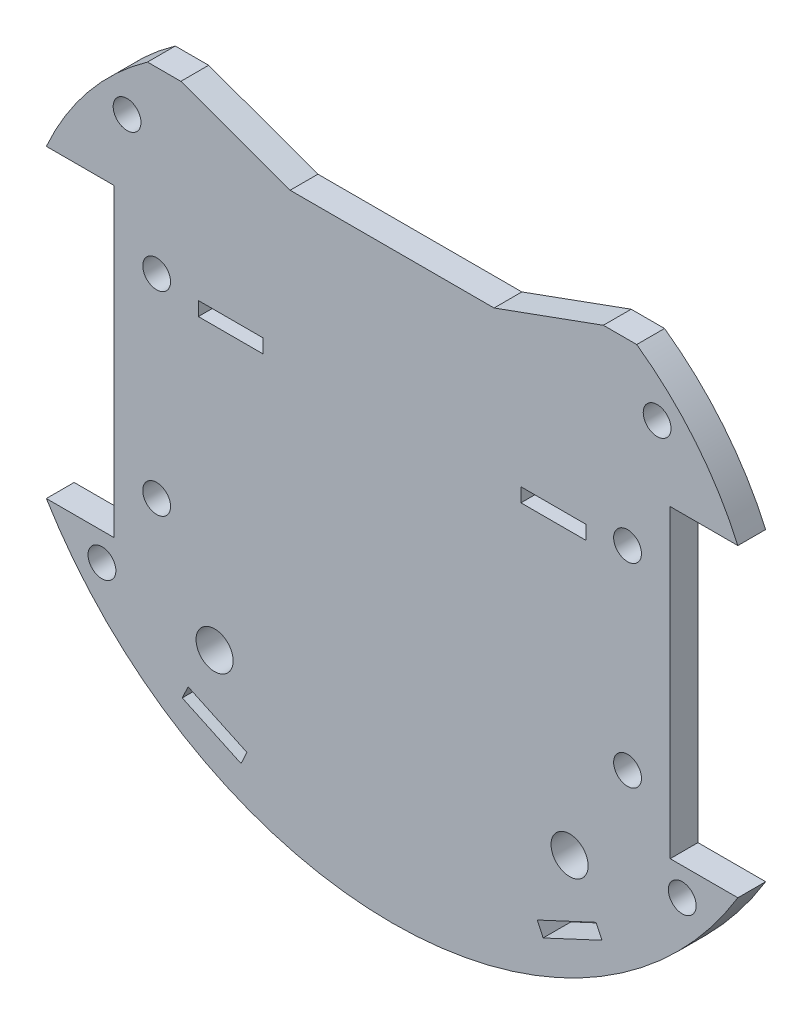
SolidWorks part; units mm, degrees
ref_plane "Front Plane" through (0, 0, 0) normal (0, 0, 1) x (1, 0, 0)
ref_plane "Top Plane" through (0, 0, 0) normal (0, 1, 0) x (1, 0, 0)
ref_plane "Right Plane" through (0, 0, 0) normal (1, 0, 0) x (0, 0, -1)
sketch "Sketch1" plane through (0, 0, 0) normal (0, 0, 1) x (1, 0, 0)
  line L2 (11, 25.5) -> (-11, 25.5)
  line L3 (-11, 25.5) -> (-22.79, 29.7803)
  line L4 (11, 25.5) -> (22.79, 29.7803)
  arc A0 (-22.79, 29.7803) -> (22.79, 29.7803) centre (0, 0) ccw
  arc A1 (-22.79, 29.7803) -> (22.79, 29.7803) centre (0, 0) ccw
  dimension "D2" = 37.5
extrude "Boss-Extrude1" add sketch "Sketch1" along normal blind 3 contours L3 A0 L4 L2
sketch "Sketch2" plane through (0, 0, 3) normal (0, 0, 1) x (1, 0, 0)
  line L0 (0, 0) -> (-25.8, 0) construction
  line L2 (0, 0) -> (0, 15.281) construction
  circle A4 centre (-25.4, 10.4969) radius 1.5
  circle A5 centre (-25.4, -10.4931) radius 1.5
  circle A6 centre (25.4, -10.4931) radius 1.5
  circle A7 centre (25.4, 10.4969) radius 1.5
  point P6 (-25.8, 0)
  dimension "D1" = 25.8
  dimension "D2" = 20.99
extrude "Cut-Extrude3" cut sketch "Sketch2" against normal blind 3
sketch "Sketch3" plane through (0, 0, 3) normal (0, 0, 1) x (1, 0, 0)
  line L1 (-30.76, 21.4493) -> (-30.76, -21.4493)
  line L3 (30.76, 21.4493) -> (30.76, -21.4493)
  arc A0 (-22.79, 29.7803) -> (22.79, 29.7803) centre (0, 0) ccw construction
  arc A1 (-30.76, 21.4493) -> (-30.76, -21.4493) centre (0, 0) ccw
  arc A2 (30.76, 21.4493) -> (30.76, -21.4493) centre (0, 0) cw
  point P10 (-30.76, 0)
extrude "Cut-Extrude4" cut sketch "Sketch3" against normal blind 10
sketch "Sketch4" plane through (0, 0, 3) normal (0, 0, 1) x (1, 0, 0)
  line L0 (-30.76, 21.4493) -> (-30.76, 16.4493) construction
  line L1 (-30.76, -21.4493) -> (-30.76, 21.4493) construction
  line L2 (30.76, 21.4493) -> (30.76, 16.4493) construction
  line L3 (30.76, 21.4493) -> (30.76, -21.4493) construction
  line L4 (-30.76, -21.4493) -> (-30.76, -16.4493) construction
  line L5 (30.76, -21.4493) -> (30.76, -16.4493) construction
  line L6 (-30.76, -16.4493) -> (-33.6997, -16.4493)
  line L7 (-30.76, 16.4493) -> (-33.6997, 16.4493)
  line L8 (30.76, 16.4493) -> (33.6997, 16.4493)
  line L9 (30.76, -16.4493) -> (33.6997, -16.4493)
  line L10 (30.76, -21.4493) -> (30.76, -16.4493)
  line L11 (30.76, 21.4493) -> (30.76, 16.4493)
  line L12 (-30.76, 16.4493) -> (-30.76, 21.4493)
  line L13 (-30.76, -21.4493) -> (-30.76, -16.4493)
  arc A0 (-33.6997, -16.4493) -> (33.6997, -16.4493) centre (0, 0) ccw
  arc A1 (-30.76, 21.4493) -> (-33.6997, 16.4493) centre (0, 0) ccw
  arc A2 (33.6997, 16.4493) -> (30.76, 21.4493) centre (0, 0) ccw
  line M2 (30.76, -21.4493) -> (30.76, 21.4493)
  line M8 (-30.76, 21.4493) -> (-30.76, -21.4493)
  dimension "D1" = 5
  dimension "D2" = 5
extrude "Boss-Extrude2" add sketch "Sketch4" against normal blind 3 contours L6 A0 M8 | A1 L7 M8 | L8 A2 M2 | A0 L9 M2
sketch "Sketch5" plane through (0, 0, 3) normal (0, 0, 1) x (1, 0, 0)
  line L0 (-30.76, 16.4493) -> (-30.2, 16.4493) construction
  line L1 (-30.76, -16.4493) -> (-30.2, -16.4493) construction
  line L2 (0, 0) -> (0, -3.3934) construction
  line L3 (-30.2, -16.4493) -> (-30.76, -16.4493)
  line L4 (-30.2, -16.4493) -> (-30.2, 16.4493)
  line L5 (-30.2, 16.4493) -> (-30.76, 16.4493)
  line L6 (-30.76, -16.4493) -> (-30.76, 16.4493)
  line L7 (30.76, -16.4493) -> (30.2, -16.4493) construction
  line L8 (30.76, 16.4493) -> (30.2, 16.4493) construction
  line L9 (30.76, -16.4493) -> (30.76, 16.4493)
  line L10 (30.2, 16.4493) -> (30.76, 16.4493)
  line L11 (30.2, -16.4493) -> (30.2, 16.4493)
  line L12 (30.2, -16.4493) -> (30.76, -16.4493)
  dimension "D2" = 0.56
extrude "Cut-Extrude5" cut sketch "Sketch5" against normal blind 3
sketch "Sketch6" plane through (0, 0, 3) normal (0, 0, 1) x (1, 0, 0)
  line L1 (-30.2, 16.4493) -> (-30, 16.4493)
  line L2 (-30.2, 16.4493) -> (-30.2, -16.4493)
  line L3 (-30.2, -16.4493) -> (-30, -16.4493)
  line L4 (-30, 16.4493) -> (-30, -16.4493)
  line L5 (30, 16.4493) -> (30, -16.4493)
  line L6 (30.2, -16.4493) -> (30, -16.4493)
  line L7 (30.2, 16.4493) -> (30.2, -16.4493)
  line L8 (30.2, 16.4493) -> (30, 16.4493)
  dimension "D1" = 0.2
extrude "Cut-Extrude6" cut sketch "Sketch6" against normal blind 3
sketch "Sketch7" plane through (0, 0, 3) normal (0, 0, 1) x (1, 0, 0)
  line L0 (0, -37.5) -> (0, -5.6) construction
  line L1 (0, -21.55) -> (-21.15, -21.55) construction
  line L2 (-21.15, -21.55) -> (-19.15, -21.55) construction
  arc A0 (-33.6997, -16.4493) -> (33.6997, -16.4493) centre (0, 0) ccw construction
  circle A1 centre (-19.15, -21.55) radius 2
  circle A2 centre (19.15, -21.55) radius 2
  dimension "D1" = 31.9
  dimension "D2" = 21.15
  dimension "D3" = 2
extrude "Cut-Extrude8" cut sketch "Sketch7" against normal blind 3 contours A1 | A2
sketch "Sketch8" plane through (0, 0, 3) normal (0, 0, 1) x (1, 0, 0)
  line L2 (-33.6997, 16.4493) -> (-37.2997, 16.4493)
  line L3 (33.6997, 16.4493) -> (37.2997, 16.4493)
  line L4 (-22.79, 29.7803) -> (-26.39, 29.7803)
  line L5 (22.79, 29.7803) -> (26.39, 29.7803)
  line L6 (0, 0) -> (0, 7.7073) construction
  arc A0 (-37.2997, 16.4493) -> (-26.39, 29.7803) centre (-7.6125, 3.2837) cw
  arc A1 (37.2997, 16.4493) -> (26.39, 29.7803) centre (7.6125, 3.2837) ccw
  arc A7 (-33.6997, 16.4493) -> (-22.79, 29.7803) centre (0, 0) cw
  arc A8 (22.79, 29.7803) -> (33.6997, 16.4493) centre (0, 0) cw
  dimension "D4" = 3.6
extrude "Boss-Extrude3" add sketch "Sketch8" against normal blind 3
sketch "Sketch9" plane through (0, 0, 3) normal (0, 0, 1) x (1, 0, 0)
  line L0 (0, 0) -> (0, 9.4958) construction
  line L1 (0, -37.5) -> (0, -37.2) construction
  line L2 (4.7339, -37.2) -> (-4.7339, -37.2)
  arc A0 (-33.6997, -16.4493) -> (33.6997, -16.4493) centre (0, 0) ccw construction
  arc A1 (-4.7339, -37.2) -> (4.7339, -37.2) centre (0, 0) ccw
  point P15 (0, -37.2)
  dimension "D1" = 0.3
extrude "Cut-Extrude9" cut sketch "Sketch9" against normal blind 3
sketch "Sketch10" plane through (0, 0, 3) normal (0, 0, 1) x (1, 0, 0)
  line L0 (-33.6997, -16.4493) -> (-37.2997, -16.4493)
  line L1 (-33.6997, -16.4493) -> (-37.2997, -16.4493) construction
  line L2 (0, 0) -> (0, 6.5031) construction
  line L3 (33.6997, -16.4493) -> (37.2997, -16.4493)
  line L4 (-4.7339, -37.2) -> (4.7339, -37.2)
  arc A0 (-37.2997, -16.4493) -> (37.2997, -16.4493) centre (0, 6.1588) ccw
  arc A1 (-33.6997, -16.4493) -> (-4.7339, -37.2) centre (0, 0) ccw
  arc A2 (33.6997, -16.4493) -> (4.7339, -37.2) centre (0, 0) cw
extrude "Boss-Extrude5" add sketch "Sketch10" against normal blind 3
sketch "Sketch11" plane through (0, 0, 3) normal (0, 0, 1) x (1, 0, 0)
  line L0 (-24.59, 29.7803) -> (-24.59, 23.7803) construction
  line L1 (-22.79, 29.7803) -> (-26.39, 29.7803) construction
  line L2 (-24.59, 23.7803) -> (-28.59, 23.7803) construction
  line L3 (0, 25.5) -> (0, 22.2803) construction
  line L4 (11, 25.5) -> (-11, 25.5) construction
  circle A0 centre (-28.59, 23.7803) radius 1.5
  circle A1 centre (28.59, 23.7803) radius 1.5
  dimension "D1" = 6
  dimension "D2" = 4
extrude "Cut-Extrude10" cut sketch "Sketch11" against normal blind 3
sketch "Sketch12" plane through (0, 0, 3) normal (0, 0, 1) x (1, 0, 0)
  line L0 (-19.15, -21.55) -> (-19.15, -28.55) construction
  line L1 (19.15, -21.55) -> (19.15, -28.55) construction
  line L2 (-22.0051, -26.3911) -> (-15.661, -29.3494)
  line L3 (-22.0051, -26.3911) -> (-22.639, -27.7506)
  line L4 (-22.639, -27.7506) -> (-16.2949, -30.7089)
  line L5 (-15.661, -29.3494) -> (-16.2949, -30.7089)
  line L6 (-22.0051, -26.3911) -> (-16.2949, -30.7089) construction
  line L7 (-22.639, -27.7506) -> (-15.661, -29.3494) construction
  line L9 (22.0051, -26.3911) -> (15.661, -29.3494)
  line L10 (22.0051, -26.3911) -> (22.639, -27.7506)
  line L11 (22.639, -27.7506) -> (16.2949, -30.7089)
  line L12 (15.661, -29.3494) -> (16.2949, -30.7089)
  line L13 (22.0051, -26.3911) -> (16.2949, -30.7089) construction
  line L14 (22.639, -27.7506) -> (15.661, -29.3494) construction
  dimension "D1" = 7
  dimension "D2" = 7
  dimension "D3" = 1.5
  dimension "D4" = 7
extrude "Cut-Extrude11" cut sketch "Sketch12" against normal blind 3
sketch "Sketch13" plane through (0, 0, 3) normal (0, 0, 1) x (1, 0, 0)
  line L0 (-25.4, 10.4969) -> (-17.4, 10.4969) construction
  line L1 (-17.4, 10.4969) -> (-17.4, 9.4969) construction
  line L2 (0, 25.5) -> (0, 21.303) construction
  line L3 (-20.9, 10.2469) -> (-13.9, 10.2469)
  line L4 (-20.9, 10.2469) -> (-20.9, 8.7469)
  line L5 (-20.9, 8.7469) -> (-13.9, 8.7469)
  line L6 (-13.9, 10.2469) -> (-13.9, 8.7469)
  line L7 (-20.9, 10.2469) -> (-13.9, 8.7469) construction
  line L8 (-20.9, 8.7469) -> (-13.9, 10.2469) construction
  line L9 (11, 25.5) -> (-11, 25.5) construction
  line L10 (20.9, 8.7469) -> (13.9, 10.2469) construction
  line L11 (20.9, 10.2469) -> (13.9, 8.7469) construction
  line L12 (17.4, 10.4969) -> (17.4, 9.4969) construction
  line L13 (13.9, 10.2469) -> (13.9, 8.7469)
  line L14 (20.9, 8.7469) -> (13.9, 8.7469)
  line L15 (20.9, 10.2469) -> (20.9, 8.7469)
  line L16 (20.9, 10.2469) -> (13.9, 10.2469)
  dimension "D1" = 8
  dimension "D2" = 1
  dimension "D3" = 7
  dimension "D4" = 1.5
extrude "Cut-Extrude12" cut sketch "Sketch13" against normal blind 3
sketch "Sketch14" plane through (0, 0, 3) normal (0, 0, 1) x (1, 0, 0)
  line L0 (-37.2997, -16.4493) -> (-31.2997, -16.4493) construction
  line L1 (-30, -16.4493) -> (-37.2997, -16.4493) construction
  line L2 (-31.2997, -16.4493) -> (-31.2997, -19.4493) construction
  line L3 (37.2997, -16.4493) -> (31.2997, -16.4493) construction
  line L4 (30, -16.4493) -> (37.2997, -16.4493) construction
  line L5 (31.2997, -16.4493) -> (31.2997, -19.4493) construction
  circle A0 centre (-31.2997, -19.4493) radius 1.5
  circle A1 centre (31.2997, -19.4493) radius 1.5
  dimension "D3" = 6
  dimension "D1" = 6
  dimension "D2" = 3
extrude "Cut-Extrude13" cut sketch "Sketch14" against normal blind 3
